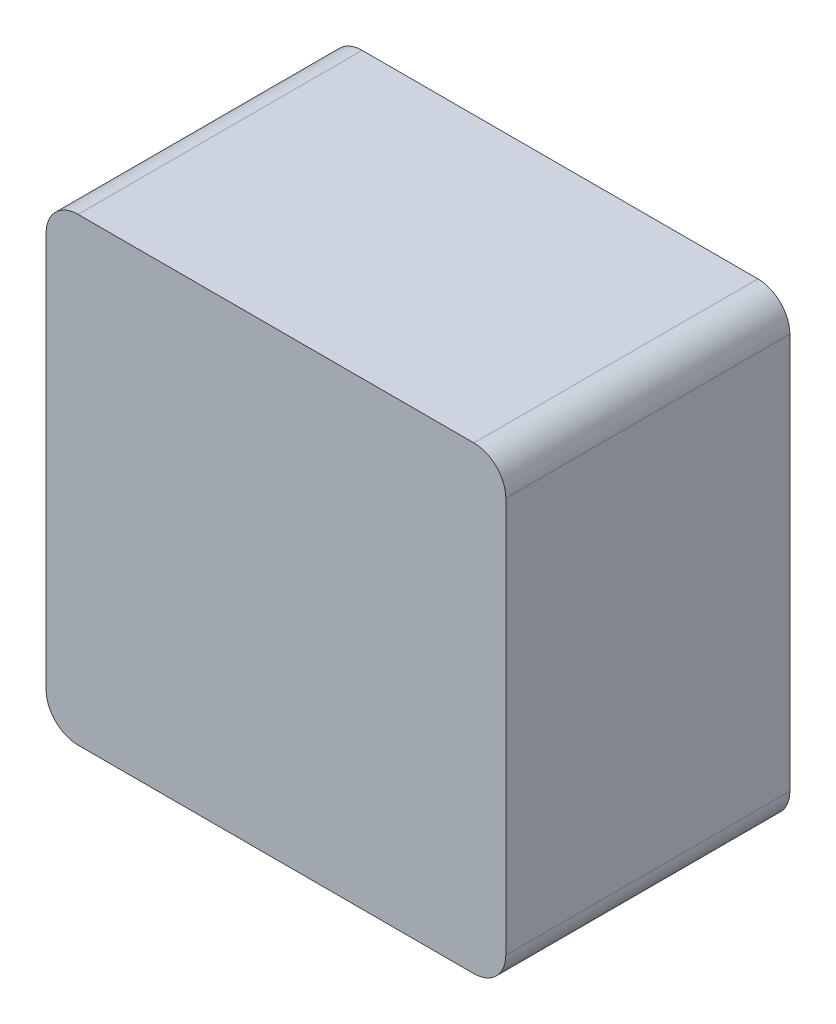
SolidWorks part; units mm, degrees
ref_plane "前视基准面" through (0, 0, 0) normal (0, 0, 1) x (1, 0, 0)
ref_plane "上视基准面" through (0, 0, 0) normal (0, 1, 0) x (1, 0, 0)
ref_plane "右视基准面" through (0, 0, 0) normal (1, 0, 0) x (0, 0, -1)
other "Configuration Table"
sketch "草图1" plane through (0, 0, 0) normal (0, 0, 1) x (1, 0, 0)
  line L1 (-36, 36) -> (36, 36)
  line L2 (-36, 36) -> (-36, -36)
  line L3 (-36, -36) -> (36, -36)
  line L4 (36, 36) -> (36, -36)
  line L5 (0, -36) -> (0, 36) construction
  line L6 (-36, 0) -> (36, 0) construction
  point P0 (0, 0)
  dimension "D1" = 72
  dimension "D2" = 72
extrude "凸台-拉伸1" add sketch "草图1" along normal blind 44.5
sketch "草图4" plane through (-36, 0, 0) normal (-1, 0, 0) x (0, 0, 1)
  line L0 (44.5, 36) -> (0, 36) construction
  line L1 (0, 36) -> (0, -36) construction
  line L2 (4, 11) -> (14, 11)
  line L3 (4, 11) -> (4, -4)
  line L4 (4, -4) -> (14, -4)
  line L5 (14, 11) -> (14, -4)
  line L6 (18, -11) -> (18, -26)
  line L7 (5, -13) -> (11, -13)
  line L8 (5, -13) -> (5, -26)
  line L9 (5, -26) -> (11, -26)
  line L10 (11, -13) -> (11, -26)
  line L11 (18, -26) -> (21, -26)
  line L12 (21, -26) -> (23.8264, -23.5)
  line L13 (23.8264, -23.5) -> (23.8264, -13.5)
  line L14 (23.8264, -13.5) -> (21, -11)
  line L15 (21, -11) -> (18, -11)
  line L16 (18, -18.5) -> (23.8264, -18.5) construction
  line L18 (18, 10.5) -> (18, -4.5)
  line L19 (18, -4.5) -> (21, -4.5)
  line L20 (21, -4.5) -> (23.8264, -2)
  line L21 (23.8264, -2) -> (23.8264, 8)
  line L22 (23.8264, 8) -> (21, 10.5)
  line L23 (21, 10.5) -> (18, 10.5)
  circle A0 centre (10, 22.5) radius 2.5
  point P30 (19.5, -11)
  dimension "D2" = 5
  dimension "D1" = 13.5
  dimension "D3" = 25
  dimension "D4" = 15
  dimension "D5" = 10
  dimension "D6" = 4
  dimension "D7" = 10
  dimension "D8" = 9
  dimension "D9" = 13
  dimension "D10" = 6
  dimension "D11" = 5
  dimension "D12" = 47
  dimension "D13" = 15
  dimension "D14" = 10
  dimension "D15" = 18
  dimension "D16" = 3
  dimension "D17" = 3
  dimension "D18" = 3.7734
  dimension "D19" = 18
  dimension "D20" = 10
  dimension "D21" = 3.7734
  dimension "D22" = 3.7734
  dimension "D23" = 3
  dimension "D24" = 3
  dimension "D25" = 6.5
extrude "切除-拉伸2" cut sketch "草图4" against normal blind 10
fillet "圆角1" radius 5 4 edges at (-36, -36, 22.25) (-36, 36, 22.25) (36, 36, 22.25) (36, -36, 22.25)
sketch "草图2" plane through (0, 0, 0) normal (0, 0, -1) x (-1, 0, 0)
  line L0 (0, 36) -> (0, -36) construction
  line L1 (-31, 36) -> (31, 36) construction
  line L2 (31, -36) -> (-31, -36) construction
  circle A0 centre (0, 27.5) radius 1.05
  circle A1 centre (0, -27.5) radius 1.05
  dimension "D1" = 2.1
  dimension "D2" = 2.1
  dimension "D3" = 8.5
  dimension "D4" = 8.5
  dimension "D5" = 55
extrude "切除-拉伸1" cut sketch "草图2" against normal blind 5
sketch "草图3" plane through (0, 0, 0) normal (0, 0, -1) x (-1, 0, 0)
  line L0 (36, 31) -> (36, -31) construction
  line L1 (-31, 36) -> (31, 36) construction
  line L2 (31, -36) -> (-31, -36) construction
  line L3 (-36, -31) -> (-36, 31) construction
  circle A8 centre (29.5, -29.5) radius 2.25
  circle A9 centre (29.5, -29.5) radius 4
  circle A10 centre (-29.5, -29.5) radius 2.25
  circle A11 centre (-29.5, -29.5) radius 4
  circle A12 centre (-29.5, 29.5) radius 2.25
  circle A13 centre (-29.5, 29.5) radius 4
  circle A14 centre (29.5, 29.5) radius 2.25
  circle A15 centre (29.5, 29.5) radius 4
  dimension "D3" = 4.5
  dimension "D4" = 6.5
  dimension "D6" = 8
  dimension "D7" = 4.5
  dimension "D8" = 4.5
  dimension "D9" = 8
  dimension "D14" = 8
  dimension "D15" = 4.5
  dimension "D2" = 8
  dimension "D10" = 6.5
  dimension "D11" = 6.5
  dimension "D12" = 6.5
  dimension "D13" = 6.5
  dimension "D16" = 6.5
  dimension "D17" = 6.5
  dimension "D5" = 6.5
extrude "凸台-拉伸2" add sketch "草图3" along normal blind 1
